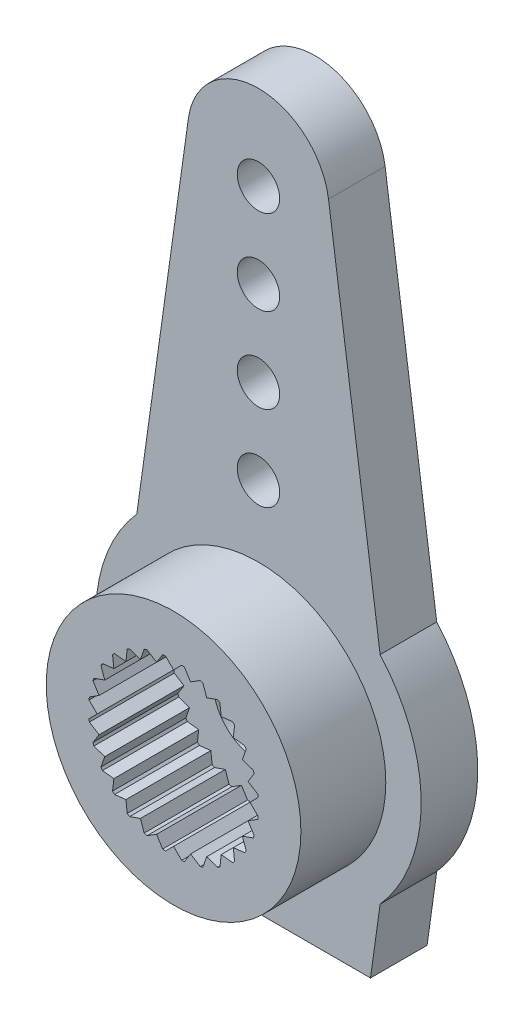
SolidWorks part; units mm, degrees
ref_plane "Plan de face" through (0, 0, 0) normal (0, 0, 1) x (1, 0, 0)
ref_plane "Plan de dessus" through (0, 0, 0) normal (0, 1, 0) x (1, 0, 0)
ref_plane "Plan de droite" through (0, 0, 0) normal (1, 0, 0) x (0, 0, -1)
sketch "Esquisse1" plane through (0, 0, 0) normal (0, 0, 1) x (1, 0, 0)
  circle A0 centre (0, 0) radius 5.75
  circle A1 centre (0, 0) radius 1.6
  dimension "D1" = 11.5
  dimension "D2" = 3.2
extrude "Boss.-Extru.1" add sketch "Esquisse1" along normal blind 5
sketch "Esquisse2" plane through (0, 0, 5) normal (0, 0, 1) x (1, 0, 0)
  circle A0 centre (0, 0) radius 3
  dimension "D1" = 6
extrude "Enlèv. mat.-Extru.1" cut sketch "Esquisse2" against normal blind 3
sketch "Esquisse3" plane through (0, 0, 5) normal (0, 0, 1) x (1, 0, 0)
  circle A0 centre (0, 0) radius 5.75
  circle A1 centre (0, 0) radius 4.5
  circle A2 centre (0, 0) radius 3 construction
  circle A3 centre (0, 0) radius 5.75 construction
  dimension "D1" = 1.5
extrude "Enlèv. mat.-Extru.2" cut sketch "Esquisse3" against normal blind 3
sketch "Esquisse4" plane through (0, 0, 0) normal (0, 0, -1) x (-1, 0, 0)
  line L0 (-4.3, 3.8174) -> (-2.4759, 16.8466)
  line L1 (2.4759, 16.8466) -> (4.3, 3.8174)
  line L2 (-5.2729, 19) -> (6.8365, 19) construction
  line L3 (0, 0) -> (0, 24.2526) construction
  circle A0 centre (0, 0) radius 5.75 construction
  arc A1 (-2.4759, 16.8466) -> (2.4759, 16.8466) centre (0, 16.5) cw
  arc A2 (-4.3, 3.8174) -> (4.3, 3.8174) centre (0, 0) cw
  dimension "D2" = 2.5
  dimension "D1" = 8.6
  dimension "D3" = 19
extrude "Boss.-Extru.2" add sketch "Esquisse4" against normal up to surface (2 mm away) up to face at (4.5, 0, 2)
pattern_circular "Répétition circulaire1" count 2 every 180 about axis through (0, 0, 0) along (0, 0, 1) of "Boss.-Extru.2"
sketch "Esquisse5" plane through (0, 0, 0) normal (0, 0, -1) x (-1, 0, 0)
  line L0 (0, 0) -> (0, 20.4605) construction
  circle A0 centre (0, 7) radius 0.75
  circle A1 centre (0, 10) radius 0.75
  circle A2 centre (0, 13) radius 0.75
  circle A3 centre (0, 16) radius 0.75
  dimension "D5" = 1.5
  dimension "D6" = 1.5
  dimension "D7" = 1.5
  dimension "D8" = 1.5
  dimension "D1" = 7
  dimension "D2" = 3
  dimension "D3" = 3
  dimension "D4" = 3
extrude "Enlèv. mat.-Extru.3" cut sketch "Esquisse5" against normal blind 3
pattern_circular "Répétition circulaire2" count 2 every 180 about axis through (0, 0, 0) along (0, 0, 1) of "Enlèv. mat.-Extru.3"
sketch "Esquisse6" plane through (0, 0, 5) normal (0, 0, 1) x (1, 0, 0)
  line L0 (-1.598, 3) -> (1.8482, 3) construction
  line L1 (0, 0) -> (0, 5.9454) construction
  line L2 (-0.3, 3) -> (0, 2.7)
  line L3 (0, 2.7) -> (0.3, 3)
  line L4 (0.3, 3) -> (-0.3, 3)
  circle A0 centre (0, 0) radius 3 construction
  dimension "D1" = 0.3
  dimension "D2" = 0.6
extrude "Boss.-Extru.3" add sketch "Esquisse6" against normal up to surface (3 mm away) up to face at (1.6, 0, 2)
pattern_circular "Répétition circulaire3" count 28 over 360 about axis through (0, 0, 0) along (0, 0, 1) of "Boss.-Extru.3"
sketch "Esquisse7" plane through (0, 0, 0) normal (0, 0, -1) x (-1, 0, 0)
  circle A0 centre (0, 0) radius 1.6
  circle A1 centre (0, 0) radius 3
  circle A2 centre (0, 0) radius 1.6 construction
  dimension "D1" = 6
extrude "Enlèv. mat.-Extru.4" cut sketch "Esquisse7" against normal blind 1
sketch "Esquisse8" plane through (0, 0, 0) normal (0, 0, -1) x (-1, 0, 0)
  circle A0 centre (0, 0) radius 3.4
  circle A1 centre (0, 0) radius 4.7
  circle A2 centre (0, 0) radius 3 construction
  dimension "D1" = 0.4
  dimension "D2" = 1.3
extrude "Enlèv. mat.-Extru.5" cut sketch "Esquisse8" against normal blind 1
sketch "Szkic1" plane through (0, 0, 0) normal (0, 0, -1) x (-1, 0, 0)
  line L1 (2.4759, -16.8466) -> (4.3, -3.8174) construction
  line L2 (3.9594, -6.25) -> (-3.9594, -6.25)
  line L3 (-4.3, -3.8174) -> (-2.4759, -16.8466) construction
  line L4 (-3.9594, -6.25) -> (-2.4759, -16.8466)
  line L5 (2.4759, -16.8466) -> (3.9594, -6.25)
  arc A1 (-2.4759, -16.8466) -> (2.4759, -16.8466) centre (0, -16.5) ccw
extrude "Wytnij-wyciągnięcie1" cut sketch "Szkic1" against normal blind 10
